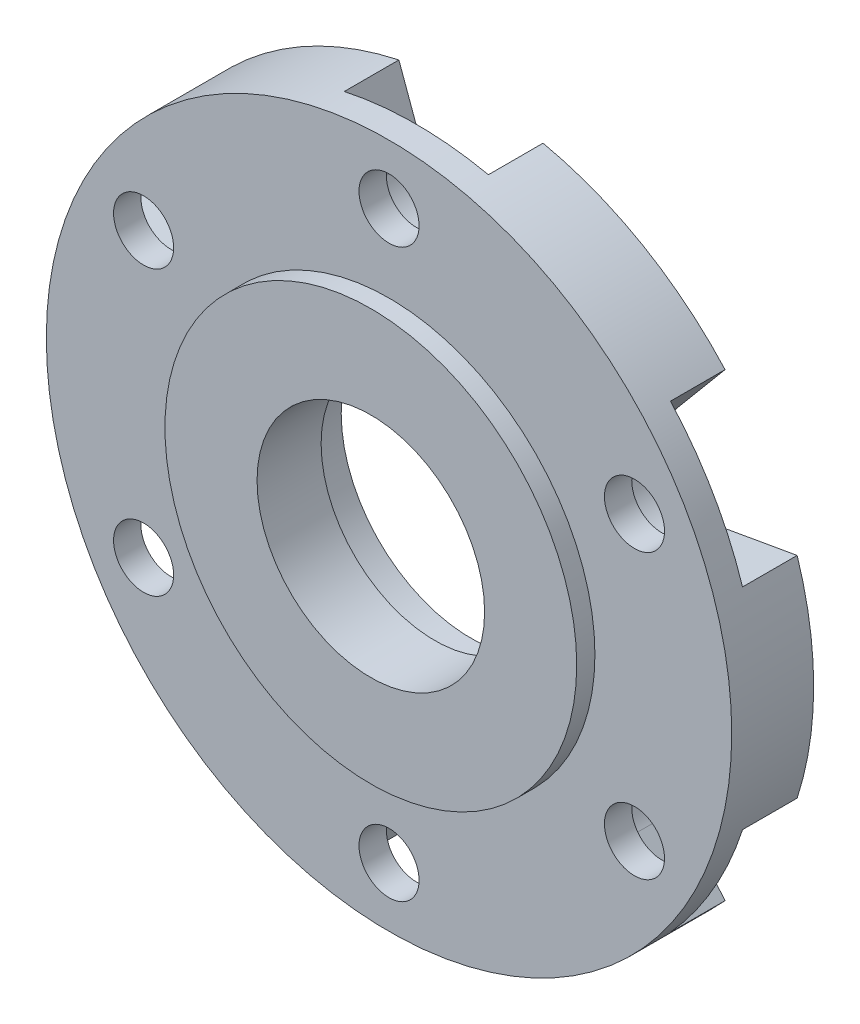
SolidWorks part; units mm, degrees
material "6061-T6 (SS)"
ref_plane "Front Plane" through (0, 0, 0) normal (0, 0, 1) x (1, 0, 0)
ref_plane "Top Plane" through (0, 0, 0) normal (0, 1, 0) x (1, 0, 0)
ref_plane "Right Plane" through (0, 0, 0) normal (1, 0, 0) x (0, 0, -1)
sketch "Sketch Spindle Skeleton" plane through (0, 0, 0) normal (1, 0, 0) x (0, 0, -1)
  line L0 (-95.847, -9.525) -> (-140.95, -9.525)
  line L5 (-1000, 0) -> (49000, 0)
  line L6 (0, -9.525) -> (0, 9.525)
  line L13 (0, 9.525) -> (-45.847, 9.525)
  line L26 (-45.847, 9.525) -> (-45.847, 14)
  line L27 (-45.847, 14) -> (-95.847, 14)
  line L32 (-95.847, 14) -> (-95.847, 9.525)
  line L34 (-160, 7) -> (-160, -7)
  line L36 (-95.847, -9.525) -> (-95.847, -14)
  line L37 (-95.847, -14) -> (-45.847, -14)
  line L38 (-45.847, -14) -> (-45.847, -9.525)
  line L39 (0, -9.525) -> (-45.847, -9.525)
  line L40 (-25.305, 37.6491) -> (-16.305, 37.6491)
  line L41 (-111.341, 22.6187) -> (-95.847, 22.6187)
  line L42 (-111.341, 22.6187) -> (-111.341, -22.6187)
  line L43 (-111.341, -22.6187) -> (-95.847, -22.6187)
  line L44 (-95.847, 22.6187) -> (-95.847, -22.6187)
  line L45 (-111.341, 22.6187) -> (-95.847, -22.6187) construction
  line L46 (-111.341, -22.6187) -> (-95.847, 22.6187) construction
  line L47 (-30.353, 22.6187) -> (-45.847, 22.6187)
  line L48 (-30.353, 22.6187) -> (-30.353, -22.6187)
  line L49 (-30.353, -22.6187) -> (-45.847, -22.6187)
  line L50 (-45.847, 22.6187) -> (-45.847, -22.6187)
  line L51 (-30.353, 22.6187) -> (-45.847, -22.6187) construction
  line L52 (-30.353, -22.6187) -> (-45.847, 22.6187) construction
  line L59 (-16.305, 37.6491) -> (-16.305, -37.6491)
  line L60 (-16.305, -37.6491) -> (-25.305, -37.6491)
  line L61 (-25.305, -22.6187) -> (-27.305, -22.6187)
  line L62 (-27.305, -22.6187) -> (-27.305, -12.5)
  line L63 (-27.305, -12.5) -> (-25.305, -12.5)
  line L64 (-25.305, -12.5) -> (-25.305, 12.5)
  line L65 (-25.305, 12.5) -> (-27.305, 12.5)
  line L66 (-27.305, 12.5) -> (-27.305, 22.6187)
  line L67 (-27.305, 22.6187) -> (-25.305, 22.6187)
  line L68 (-25.305, 22.6187) -> (-25.305, 37.6491)
  line L69 (-25.305, -22.6187) -> (-25.305, -37.6491)
  line L71 (-119.469, 37.6491) -> (-26.305, 37.6491)
  line L72 (-119.469, 37.6491) -> (-119.469, -37.6491)
  line L73 (-119.469, -37.6491) -> (-26.305, -37.6491)
  line L74 (-26.305, 37.6491) -> (-26.305, -37.6491)
  line L75 (-119.469, 37.6491) -> (-26.305, -37.6491) construction
  line L76 (-119.469, -37.6491) -> (-26.305, 37.6491) construction
  line L77 (-140.95, -9.525) -> (-140.95, -7)
  line L78 (-140.95, -7) -> (-160, -7)
  line L79 (-95.847, 9.525) -> (-140.95, 9.525)
  line L80 (-140.95, 7) -> (-160, 7)
  line L81 (-140.95, 9.525) -> (-140.95, 7)
  line L82 (-118.3985, 9.525) -> (-118.3985, -9.525) construction
  line L83 (-22.9235, 9.525) -> (-22.9235, -9.525) construction
  line L96 (-119.469, 37.6492) -> (-134.709, 37.6492)
  line L98 (-119.469, -37.6491) -> (-134.709, -37.6491)
  line L99 (-134.709, 37.6492) -> (-134.709, -37.6491)
  line L110 (-119.469, 37.6492) -> (-119.469, -37.6491)
  point P3 (0, 0)
  point P18 (-103.594, 0)
  point P24 (-38.1, 0)
  point P29 (-72.887, 0)
  point P48 (-16.305, 31.1339)
  point P58 (0, 0)
  point P59 (0, 0)
  point P70 (-134.709, 31.1339)
revolve "Main Revolve" add sketch "Sketch Spindle Skeleton" angle 360 about L5
sketch "Sketch Center Cut" plane through (0, 0, 25.305) normal (0, 0, 1) x (1, 0, 0)
  circle A3 centre (0, 0) radius 12.5
  dimension "D1" = 25
extrude "Cut Center" cut sketch "Sketch Center Cut" against normal through all both and the other way through all
hole_wizard "CBORE for M6 SHCS1" positions "Hole wizard sketch 1" profile "Hole wizard sketch 2" counterbore size "M6" standard "ANSI Metric" end condition through all
sketch "Hole wizard sketch 1" plane through (0, 0, 16.305) normal (0, 0, -1) x (-1, 0, 0)
  point P0 (0, 31.1339)
sketch "Hole wizard sketch 2" plane through (0, 31.1339, 16.305) normal (1, 0, 0) x (0, 1, 0)
  line L0 (0, 0) -> (0, 11)
  line L1 (0, 11) -> (3.3, 11)
  line L3 (3.3, 11) -> (3.3, 6)
  line L4 (3.3, 6) -> (5.5, 6)
  line L5 (5.5, 6) -> (5.5, 0)
  line L7 (5.5, 0) -> (0, 0)
  line L11 (0, -6.35) -> (0, 107.95) construction
  dimension "Thru Hole Dia." = 6.6
  dimension "Thru Hole Depth" = 11
  dimension "C'Bore Dia." = 11
  dimension "C'Bore Depth" = 6
pattern_circular "CirPattern1" count 6 over 360 about axis through (0, 0, 0) along (0, 0, 1) of "CBORE for M6 SHCS1"
sketch "Sketch1" plane through (0, 0, 16.305) normal (0, 0, -1) x (-1, 0, 0)
  circle A0 centre (0, 0) radius 14.2558
  dimension "D1" = 28.5115
extrude "Cut-Extrude1" cut sketch "Sketch1" against normal blind 3.9624
sketch "Sketch2" plane through (0, 0, 16.305) normal (0, 0, -1) x (-1, 0, 0)
  line L0 (-5.1683, 29.2528) -> (-7.9179, 36.8071)
  line L1 (0, 31.1339) -> (0, 37.65) construction
  line L2 (5.1683, 29.2528) -> (7.9179, 36.8071)
  circle A0 centre (0, 31.1339) radius 5.5 construction
  circle A1 centre (0, 0) radius 37.6491 construction
  arc A2 (-5.1683, 29.2528) -> (5.1683, 29.2528) centre (0, 31.1339) ccw
  point P37 (0.065, 0.0375)
  circle M8 centre (0, 31.1339) radius 5.5
  circle M9 centre (0, 0) radius 37.6491
  dimension "D1" = 20
extrude "Cut-Extrude2" cut sketch "Sketch2" against normal up to surface (6 mm away) contours L1 L2 M8 M9 | L1 L0 M8 M9 up to face at (23.6628, -15.567, 22.305)
pattern_circular "CirPattern2" count 6 over 360 about axis through (0, 0, 0) along (0, 0, 1) of "Cut-Extrude2"
